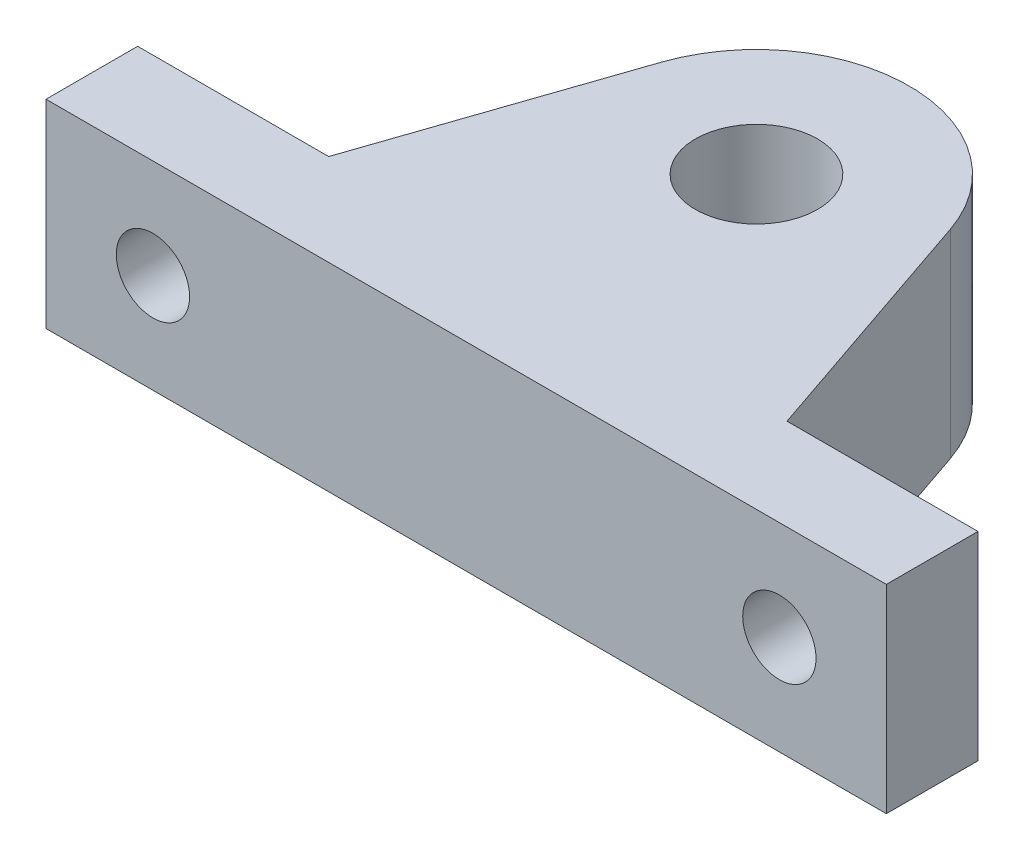
SolidWorks part; units mm, degrees
ref_plane "前视基准面" through (0, 0, 0) normal (0, 0, 1) x (1, 0, 0)
ref_plane "上视基准面" through (0, 0, 0) normal (0, 1, 0) x (1, 0, 0)
ref_plane "右视基准面" through (0, 0, 0) normal (1, 0, 0) x (0, 0, -1)
sketch "草图1" plane through (0, 0, 0) normal (0, 1, 0) x (1, 0, 0)
  line L0 (-15, 3) -> (-9.4646, 19.2283)
  line L1 (-27.5, -3) -> (27.5, -3)
  line L2 (-27.5, -3) -> (-27.5, 3)
  line L3 (-27.5, 3) -> (-15, 3)
  line L4 (27.5, -3) -> (27.5, 3)
  line L5 (-27.5, -3) -> (27.5, 3) construction
  line L6 (-27.5, 3) -> (27.5, -3) construction
  line L7 (0, 16) -> (0, 50016) construction
  line L8 (15, 3) -> (9.4646, 19.2283)
  line L9 (15, 3) -> (27.5, 3)
  circle A1 centre (0, 16) radius 4
  arc A2 (9.4646, 19.2283) -> (-9.4646, 19.2283) centre (0, 16) ccw
  point P0 (0, 0)
  point P8 (0, 26)
  point P16 (0, 26)
  dimension "D3" = 8
  dimension "D1" = 6
  dimension "D2" = 55
  dimension "D4" = 19
  dimension "D5" = 29
  dimension "D6" = 30
extrude "凸台-拉伸1" add sketch "草图1" along normal mid plane 13
ref_plane "基准面1" through (0, 3.5, 0) normal (0, 1, 0) x (1, 0, 0)
sketch "草图3" plane through (0, 3.5, 0) normal (0, 1, 0) x (1, 0, 0)
  circle A0 centre (0, 16) radius 6.5
  dimension "D1" = 13
extrude "凸台-拉伸2" add sketch "草图3" against normal blind 12
sketch "草图2" plane through (0, 0, -3) normal (0, 0, -1) x (-1, 0, 0)
  line L0 (-27.5, 6.5) -> (-27.5, -6.5) construction
  line L1 (0, 0) -> (0, 50000) construction
  circle A0 centre (20.5, 0) radius 2.4
  circle A1 centre (-20.5, 0) radius 2.4
  point P8 (-27.5, 0)
  dimension "D2" = 4.8
  dimension "D1" = 41
extrude "切除-拉伸1" cut sketch "草图2" against normal blind 16
sketch "草图4" plane through (0, 3.5, 0) normal (0, 1, 0) x (1, 0, 0)
  circle A0 centre (0, 16) radius 4
  circle A1 centre (0, 16) radius 4 construction
extrude "切除-拉伸2" cut sketch "草图4" against normal blind 12
